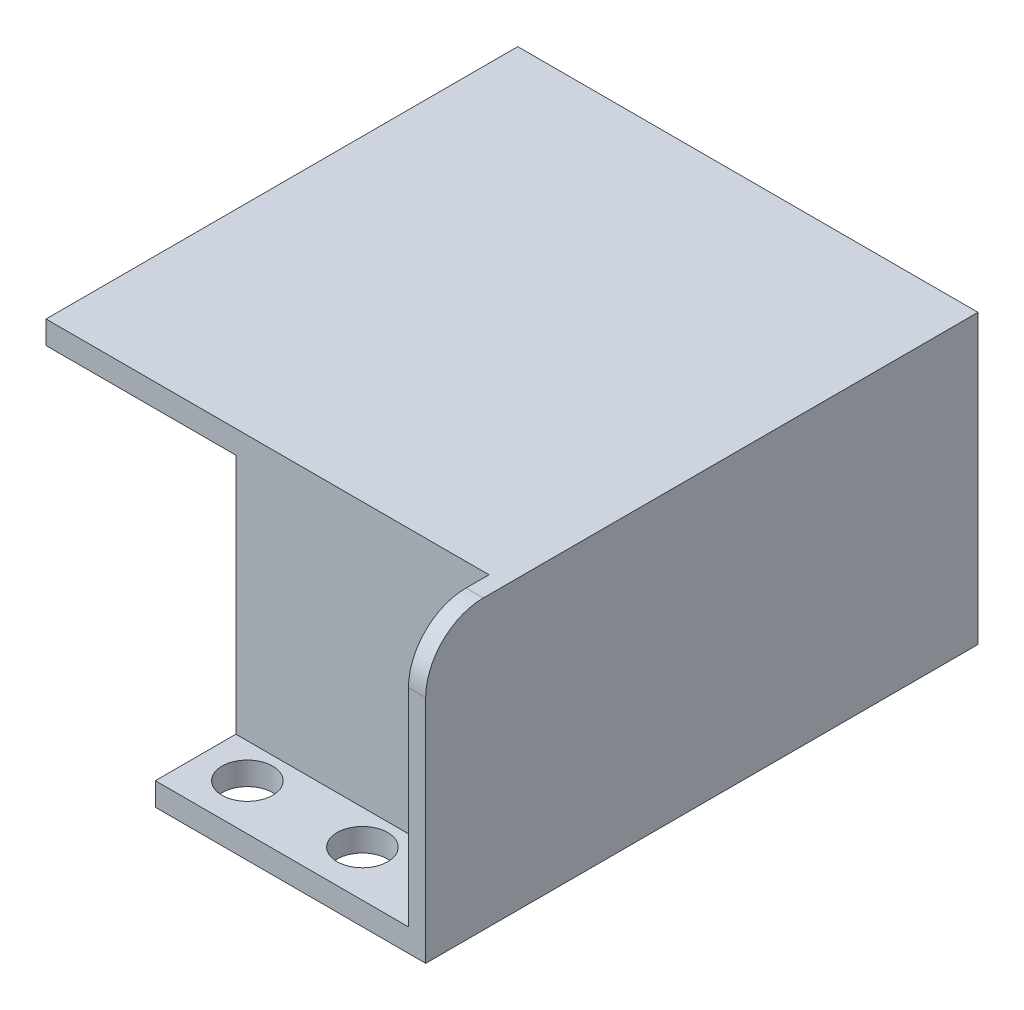
SolidWorks part; units mm, degrees
ref_plane "前视基准面" through (0, 0, 0) normal (0, 0, 1) x (1, 0, 0)
ref_plane "上视基准面" through (0, 0, 0) normal (0, 1, 0) x (1, 0, 0)
ref_plane "右视基准面" through (0, 0, 0) normal (1, 0, 0) x (0, 0, -1)
sketch "Sketch1" plane through (0, 0, 0) normal (1, 0, 0) x (0, 0, -1)
  line L0 (-8, -25) -> (0, -25)
  line L1 (0, -25) -> (0, 0)
  line L2 (-1, 0) -> (0, 0)
  line L5 (-1, 0) -> (-1, -23)
  line L6 (-1, -23) -> (-8, -23)
  line L7 (-8, -23) -> (-8, -25)
  dimension "D1" = 2
  dimension "D2" = 8
  dimension "D3" = 1
  dimension "D6" = 25
extrude "Boss-Extrude1" add sketch "Sketch1" along normal blind 22
sketch "Sketch4" plane through (22, 0, 0) normal (1, 0, 0) x (0, 0, -1)
  line L0 (0, -25) -> (0, 0) construction
  line L1 (-8, -25) -> (40, -25)
  line L2 (-8, -25) -> (-8, 0)
  line L3 (-8, 0) -> (40, 0)
  line L4 (40, -25) -> (40, 0)
  line L5 (0, 0) -> (-1, 0) construction
  dimension "D1" = 40
extrude "Boss-Extrude3" add sketch "Sketch4" along normal blind 1.5
sketch "Sketch5" plane through (0, 0, 0) normal (0, 1, 0) x (1, 0, 0)
  line L0 (22, -1) -> (0, -1) construction
  line L1 (23.5, 40) -> (-16.5, 40)
  line L2 (23.5, 40) -> (23.5, -1)
  line L3 (23.5, -1) -> (-16.5, -1)
  line L4 (-16.5, 40) -> (-16.5, -1)
  dimension "D1" = 40
extrude "Boss-Extrude4" add sketch "Sketch5" against normal blind 2
sketch "Sketch6" plane through (0, -25, 0) normal (0, -1, 0) x (1, 0, 0)
  line L0 (22, 0) -> (0, 0) construction
  line L3 (22, -40) -> (22, 0) construction
  circle A0 centre (14, 4) radius 2.2
  point P6 (21.5, 7.0798)
  dimension "D1" = 4
  dimension "D3" = 4.4
  dimension "D2" = 8
extrude "Cut-Extrude2" cut sketch "Sketch6" against normal up to next
pattern_linear "LPattern2" count 2 spacing 10 along (-1, 0, 0) of "Cut-Extrude2"
fillet "Fillet2" radius 5 1 edges at (22.75, 0, 8)
